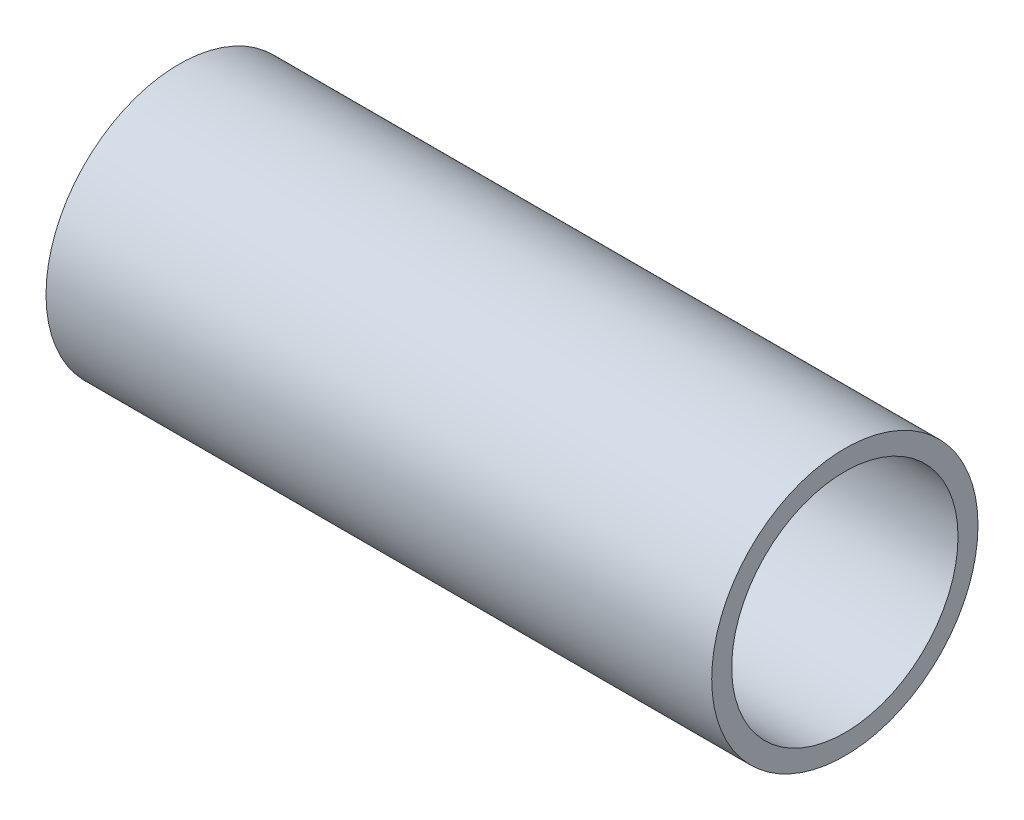
SolidWorks part; units mm, degrees
ref_plane "Front Plane" through (0, 0, 0) normal (0, 0, 1) x (1, 0, 0)
ref_plane "Top Plane" through (0, 0, 0) normal (0, 1, 0) x (1, 0, 0)
ref_plane "Right Plane" through (0, 0, 0) normal (1, 0, 0) x (0, 0, -1)
sketch "Sketch1" plane through (0, 0, 0) normal (1, 0, 0) x (0, 0, -1)
  circle A0 centre (0, 0) radius 20
  dimension "D1" = 40
extrude "Boss-Extrude1" add sketch "Sketch1" along normal blind 100
sketch "Sketch2" plane through (100, 0, 0) normal (1, 0, 0) x (0, 0, -1)
  circle A1 centre (0, 0) radius 17
  circle A2 centre (0, 0) radius 17
  circle A3 centre (0, 0) radius 17 construction
  dimension "D1" = 3
extrude "Cut-Extrude1" cut sketch "Sketch2" against normal blind 95
